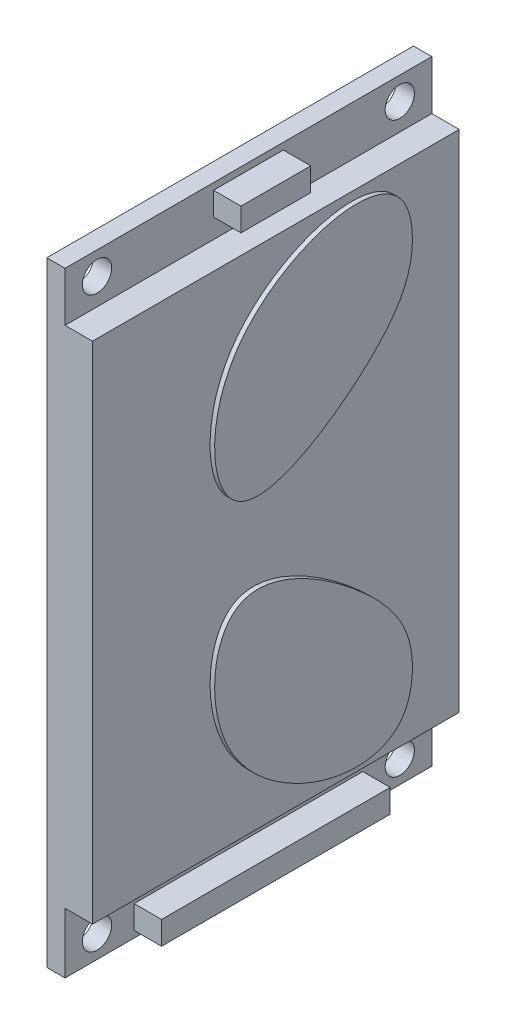
SolidWorks part; units mm, degrees
ref_plane "Front Plane" through (0, 0, 0) normal (0, 0, 1) x (1, 0, 0)
ref_plane "Top Plane" through (0, 0, 0) normal (0, 1, 0) x (1, 0, 0)
ref_plane "Right Plane" through (0, 0, 0) normal (1, 0, 0) x (0, 0, -1)
sketch "Sketch1" plane through (0, 0, 0) normal (1, 0, 0) x (0, 0, -1)
  line L0 (0, -124.0643) -> (0, 124.0643) construction
  line L1 (-20.05, -33.6) -> (20.05, -33.6)
  line L2 (-20.05, -33.6) -> (-20.05, 33.6)
  line L3 (-20.05, 33.6) -> (20.05, 33.6)
  line L4 (20.05, -33.6) -> (20.05, 33.6)
  line L5 (-20.05, -33.6) -> (20.05, 33.6) construction
  line L6 (-20.05, 33.6) -> (20.05, -33.6) construction
  circle A0 centre (16.55, 31.1) radius 1.6
  circle A1 centre (16.55, -31.11) radius 1.6
  circle A2 centre (-16.55, -31.11) radius 1.6
  circle A3 centre (-16.55, 31.1) radius 1.6
  point P0 (0, 0)
  point P13 (0, 0)
  dimension "D3" = 62.21
  dimension "D4" = 2.5
  dimension "D5" = 3.5
  dimension "D6" = 3.2
  dimension "D1" = 40.1
  dimension "D2" = 67.2
extrude "Boss-Extrude1" add sketch "Sketch1" along normal blind 2
sketch "Sketch2" plane through (2, 0, 0) normal (1, 0, 0) x (0, 0, -1)
  line L0 (-20.05, 33.6) -> (-20.05, -33.6) construction
  line L1 (-20.05, 28.2) -> (20.05, 28.2)
  line L2 (-20.05, 28.2) -> (-20.05, -27)
  line L3 (-20.05, -27) -> (20.05, -27)
  line L4 (20.05, 28.2) -> (20.05, -27)
  line L5 (20.05, -33.6) -> (20.05, 33.6) construction
  line L6 (20.05, 33.6) -> (-20.05, 33.6) construction
  line L7 (-20.05, -33.6) -> (20.05, -33.6) construction
  line L8 (-12.5, -30.33) -> (12.5, -30.33)
  line L9 (-12.5, -30.33) -> (-12.5, -32.87)
  line L10 (-12.5, -32.87) -> (12.5, -32.87)
  line L11 (12.5, -30.33) -> (12.5, -32.87)
  line L13 (-3.81, 32.87) -> (3.81, 32.87)
  line L14 (-3.81, 32.87) -> (-3.81, 30.33)
  line L15 (-3.81, 30.33) -> (3.81, 30.33)
  line L16 (3.81, 32.87) -> (3.81, 30.33)
  point P14 (12.5, -31.6)
  point P18 (-12.5, -31.6)
  point P19 (-3.81, 31.6)
  point P23 (0, 30.33)
  point P25 (0, -32.87)
  dimension "D1" = 55.2
  dimension "D2" = 5.4
  dimension "D3" = 2
  dimension "D4" = 40.1
  dimension "D5" = 2.54
  dimension "D6" = 25
  dimension "D7" = 2.54
  dimension "D8" = 2
  dimension "D9" = 7.62
extrude "Boss-Extrude2" add sketch "Sketch2" along normal blind 3
sketch "Sketch3" plane through (5, 0, 0) normal (1, 0, 0) x (0, 0, -1)
  line L0 (-79.4514, 0.6) -> (39.3514, 0.6) construction
  line L2 (-20.05, 28.2) -> (-20.05, -27) construction
  spline S0 degree 3 poles (-7.1282, 1.2925) (9.1935, -8.8094) (15.0117, -16.6006) (13.415, -29.6712) (-8.8948, -22.7987) (-7.1282, 1.2925) (9.1935, -8.8094) (15.0117, -16.6006) knots -0.766284 -0.459 -0.241212 0 0.152454 0.233716 0.541 0.758788 1 1.152454 1.233716 1.541 only from (9.4282, -10.2586) to (9.4282, -10.2586)
  spline S1 degree 3 poles (-7.1282, -0.0925) (9.1935, 10.0094) (15.0117, 17.8006) (13.415, 30.8712) (-8.8948, 23.9987) (-7.1282, -0.0925) (9.1935, 10.0094) (15.0117, 17.8006) knots -0.766284 -0.459 -0.241212 0 0.152454 0.233716 0.541 0.758788 1 1.152454 1.233716 1.541 only from (9.4282, 11.4586) to (9.4282, 11.4586)
  point P8 (-20.05, 0.6)
  dimension "D1" = 5
extrude "Boss-Extrude3" add sketch "Sketch3" along normal blind 0.5
